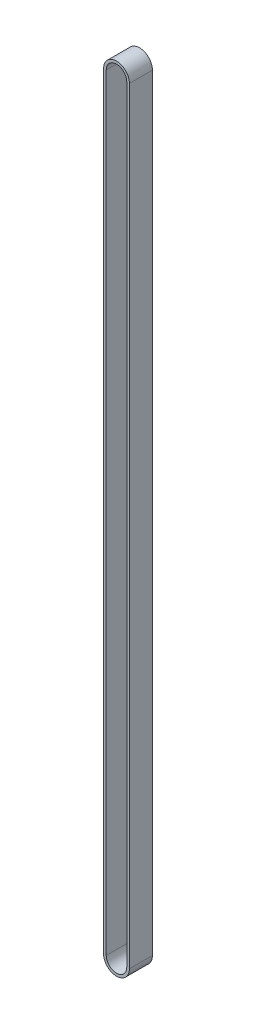
SolidWorks part; units mm, degrees
ref_plane "Front Plane" through (0, 0, 0) normal (0, 0, 1) x (1, 0, 0)
ref_plane "Top Plane" through (0, 0, 0) normal (0, 1, 0) x (1, 0, 0)
ref_plane "Right Plane" through (0, 0, 0) normal (1, 0, 0) x (0, 0, -1)
sketch "Sketch1" plane through (0, 0, 0) normal (0, 0, 1) x (1, 0, 0)
  line L0 (-6.365, 0) -> (-6.365, -400)
  line L1 (6.365, -400) -> (6.365, 0)
  arc A0 (6.365, 0) -> (-6.365, 0) centre (0, 0) ccw
  arc A1 (-6.365, -400) -> (6.365, -400) centre (0, -400) ccw
  dimension "D1" = 12.73
  dimension "D2" = 400
extrude "Extrude-Thin1" add sketch "Sketch1" along normal blind 12 thin
